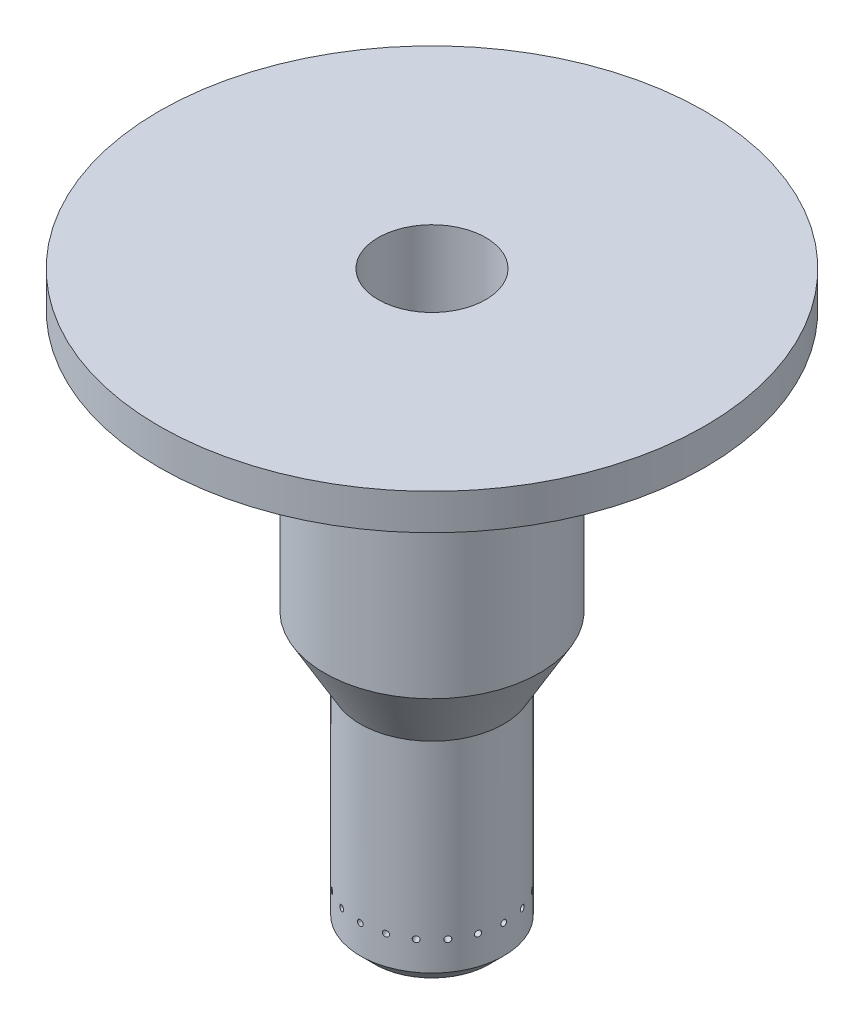
SolidWorks part; units mm, degrees
ref_plane "Front Plane" through (0, 0, 0) normal (0, 0, 1) x (1, 0, 0)
ref_plane "Top Plane" through (0, 0, 0) normal (0, 1, 0) x (1, 0, 0)
ref_plane "Right Plane" through (0, 0, 0) normal (1, 0, 0) x (0, 0, -1)
sketch "Sketch1" plane through (0, 0, 0) normal (0, 0, 1) x (1, 0, 0)
  line L0 (0, 0) -> (0, 53.1555) construction
  line L1 (6.35, 0) -> (6.35, 19.05)
  line L2 (6.35, 0) -> (0, 0)
  line L4 (0, 50.8) -> (0, 0)
  line L5 (6.35, 19.05) -> (9.525, 24.5493)
  line L6 (9.525, 24.5493) -> (9.525, 47.625)
  line L7 (9.525, 50.8) -> (0, 50.8)
  line L8 (9.525, 50.8) -> (24.1554, 50.8)
  line L9 (24.1554, 50.8) -> (24.1554, 47.625)
  line L10 (24.1554, 47.625) -> (9.525, 47.625)
  dimension "D1" = 12.7
  dimension "D2" = 50.8
  dimension "D3" = 19.05
  dimension "D4" = 30
  dimension "D5" = 19.05
  dimension "D6" = 48.3108
  dimension "D7" = 3.175
revolve "Revolve1" add sketch "Sketch1" angle 360 about L0
chamfer "Chamfer1" distance 1.27 angle 45 1 edges at (0, 0, -6.35)
hole_wizard "#76 (0.02) Diameter Hole1" positions "3DSketch1" profile "Sketch3" hole size "#76" standard "ANSI Inch"
sketch3d "3DSketch1"
  point P0 (6.35, 3.81, 0)
  dimension "D1" = 3.81
sketch "Sketch3" plane through (6.35, 3.81, 0) normal (0, 1, 0) x (0, 0, -1)
  line L0 (0, 0) -> (0, 2.6926)
  line L1 (0, 2.6926) -> (0.254, 2.54)
  line L2 (0.254, 2.54) -> (0.254, 0)
  line L5 (0.254, 0) -> (0, 0)
  line L10 (0, 2.6926) -> (-0.254, 2.54) construction
  line L11 (0, -6.35) -> (0, 107.95) construction
  dimension "Hole Dia." = 0.508
  dimension "Hole Depth" = 2.54
  dimension "Drill Angle" = 118
pattern_circular "CirPattern2" count 20 over 360 about axis through (0, 0, 0) along (0, -1, 0) of "#76 (0.02) Diameter Hole1"
hole_wizard "3/8 (0.375) Diameter Hole2" positions "Sketch6" profile "Sketch7" hole size "3/8" standard "ANSI Inch"
sketch "Sketch6" plane through (0, 50.8, 0) normal (0, 1, 0) x (1, 0, 0)
  point P0 (0, 0)
sketch "Sketch7" plane through (0, 50.8, 0) normal (1, 0, 0) x (0, 0, 1)
  line L0 (0, 0) -> (0, 49.8516)
  line L1 (0, 49.8516) -> (4.7625, 46.99)
  line L2 (4.7625, 46.99) -> (4.7625, 0)
  line L5 (4.7625, 0) -> (0, 0)
  line L10 (0, 49.8516) -> (-4.7625, 46.99) construction
  line L11 (0, -6.35) -> (0, 107.95) construction
  dimension "Hole Dia." = 9.525
  dimension "Hole Depth" = 46.99
  dimension "Drill Angle" = 118
